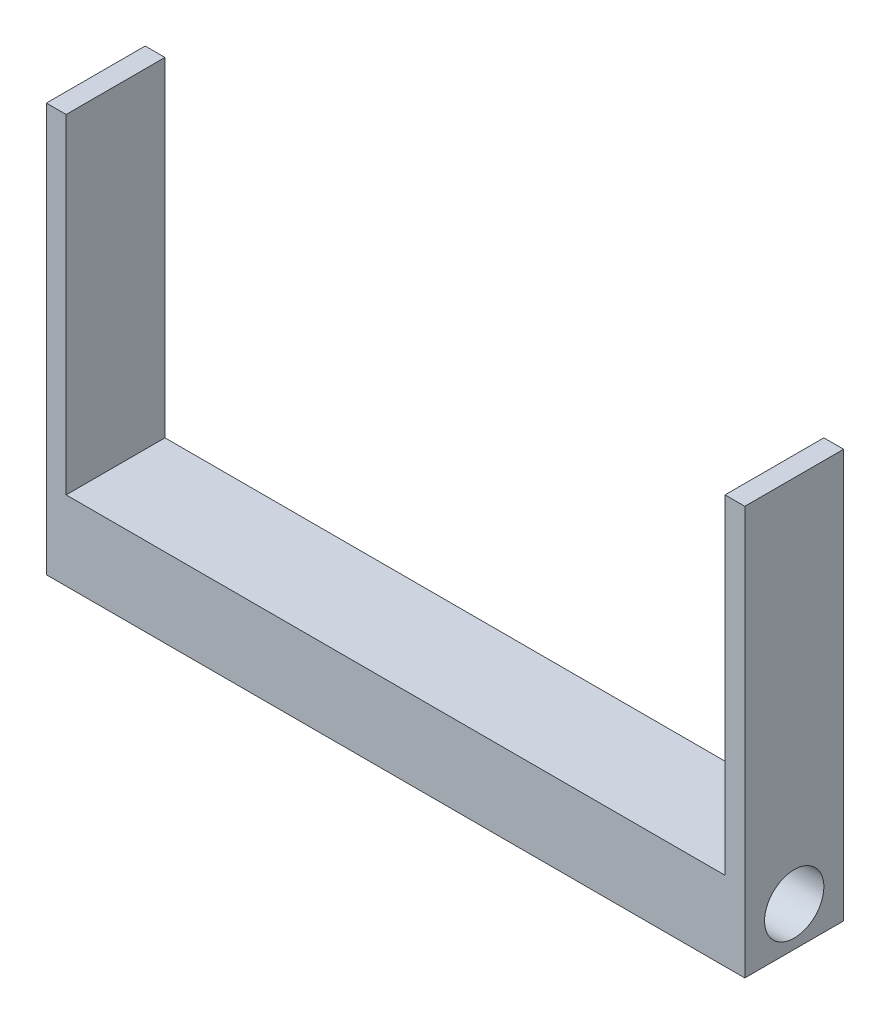
SolidWorks part; units mm, degrees
material "PLA"
ref_plane "Front Plane" through (0, 0, 0) normal (0, 0, 1) x (1, 0, 0)
ref_plane "Top Plane" through (0, 0, 0) normal (0, 1, 0) x (1, 0, 0)
ref_plane "Right Plane" through (0, 0, 0) normal (1, 0, 0) x (0, 0, -1)
sketch "Sketch1" plane through (0, 0, 0) normal (0, 0, 1) x (1, 0, 0)
  line L0 (-50, 0) -> (-50, -50)
  line L1 (-50, -50) -> (50, -50)
  line L2 (50, -50) -> (50, 0)
  dimension "D1" = 50
  dimension "D2" = 100
  dimension "D3" = 50
  dimension "D4" = 50
extrude "Extrude-Thin1" add sketch "Sketch1" along normal mid plane 15 thin
sketch "Sketch4" plane through (0, -53, 0) normal (0, -1, 0) x (1, 0, 0)
  line L4 (-53, -7.5) -> (53, -7.5)
  line L5 (53, -7.5) -> (53, 7.5)
  line L6 (53, 7.5) -> (-53, 7.5)
  line L7 (-53, 7.5) -> (-53, -7.5)
  line L8 (-53, -7.5) -> (53, -7.5)
  line L9 (53, -7.5) -> (53, 7.5)
  line L10 (53, 7.5) -> (-53, 7.5)
  line L11 (-53, 7.5) -> (-53, -7.5)
  dimension "D1" = 0
extrude "Boss-Extrude1" add sketch "Sketch4" along normal blind 9
sketch "Sketch5" plane through (53, 0, 0) normal (1, 0, 0) x (0, 0, -1)
  line L0 (7.5, -62) -> (-7.5, -62) construction
  line L1 (-7.5, -62) -> (-7.5, 0) construction
  circle A0 centre (0, -56) radius 4.5
  dimension "D1" = 9
  dimension "D2" = 6
  dimension "D3" = 7.5
extrude "Cut-Extrude1" cut sketch "Sketch5" against normal through all
